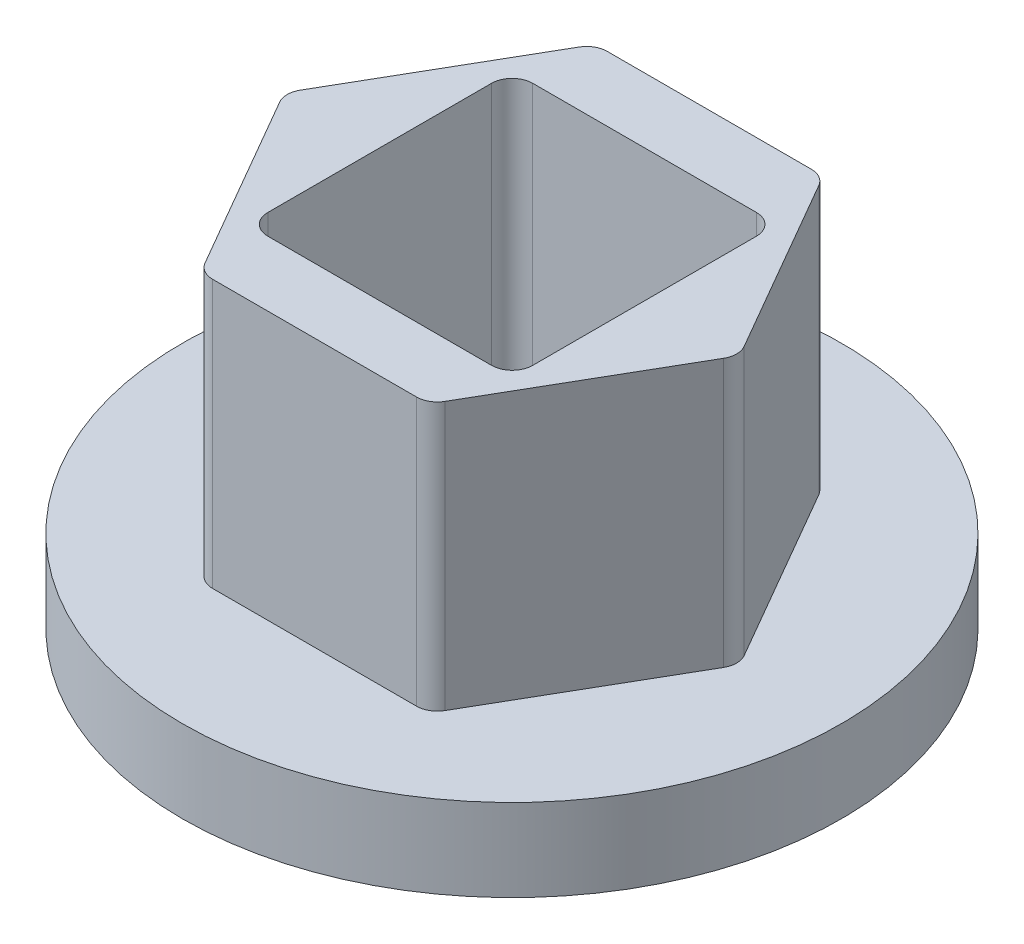
SolidWorks part; units mm, degrees
ref_plane "Front Plane" through (0, 0, 0) normal (0, 0, 1) x (1, 0, 0)
ref_plane "Top Plane" through (0, 0, 0) normal (0, 1, 0) x (1, 0, 0)
ref_plane "Right Plane" through (0, 0, 0) normal (1, 0, 0) x (0, 0, -1)
sketch "Sketch1" plane through (0, 0, 0) normal (0, 1, 0) x (1, 0, 0)
  line L0 (0, 0) -> (0, 4.5288) construction
  line L2 (-3.21, 7.7438) -> (3.22, 7.7438)
  line L3 (-3.21, 7.7438) -> (-3.21, 1.3138)
  line L4 (-3.21, 1.3138) -> (3.22, 1.3138)
  line L5 (3.22, 7.7438) -> (3.22, 1.3138)
  dimension "D1" = 6.43
  dimension "D2" = 6.43
  dimension "D3" = 3.215
  dimension "D4" = 3.22
sketch "Sketch3" plane through (0, 0, 0) normal (0, 1, 0) x (1, 0, 0)
  line L0 (0, 4.5288) -> (4.79, 4.5288) construction
  line L1 (0, 4.5288) -> (-4.79, 4.5288) construction
  line L2 (0, 4.5288) -> (0, 9.3188) construction
  line L3 (0, 4.5288) -> (0, -0.2612) construction
  line L5 (2.7655, -0.2612) -> (5.531, 4.5288)
  line L6 (5.531, 4.5288) -> (2.7655, 9.3188)
  line L7 (2.7655, 9.3188) -> (-2.7655, 9.3188)
  line L8 (-2.7655, 9.3188) -> (-5.531, 4.5288)
  line L9 (-5.531, 4.5288) -> (-2.7655, -0.2612)
  line L10 (-2.7655, -0.2612) -> (2.7655, -0.2612)
  circle A0 centre (0, 4.5288) radius 4.79 construction
  dimension "D1" = 4.79
  dimension "D2" = 4.79
  dimension "D3" = 4.79
  dimension "D4" = 4.79
  dimension "D5" = 90
  dimension "D6" = 4.79
extrude "Boss-Extrude2" add sketch "Sketch3" along normal blind 6.5
sketch "Sketch4" plane through (0, 0, 0) normal (0, 1, 0) x (1, 0, 0)
  circle A0 centre (0, 4.5288) radius 8
  dimension "D1" = 16
extrude "Boss-Extrude3" add sketch "Sketch4" against normal blind 2
extrude "Cut-Extrude1" cut sketch "Sketch1" against normal blind 2.37 and the other way blind 7.37 contours L3 L4 L5 L2
fillet "Fillet1" radius 0.5 4 edges at (3.22, 2.25, -1.3138) (3.22, 2.25, -7.7438) (-3.21, 2.25, -7.7438) (-3.21, 2.25, -1.3138)
fillet "Fillet2" radius 0.5 6 edges at (-5.531, 3.25, -4.5288) (-2.7655, 3.25, -9.3188) (2.7655, 3.25, -9.3188) (5.531, 3.25, -4.5288) (2.7655, 3.25, 0.2612) (-2.7655, 3.25, 0.2612)
